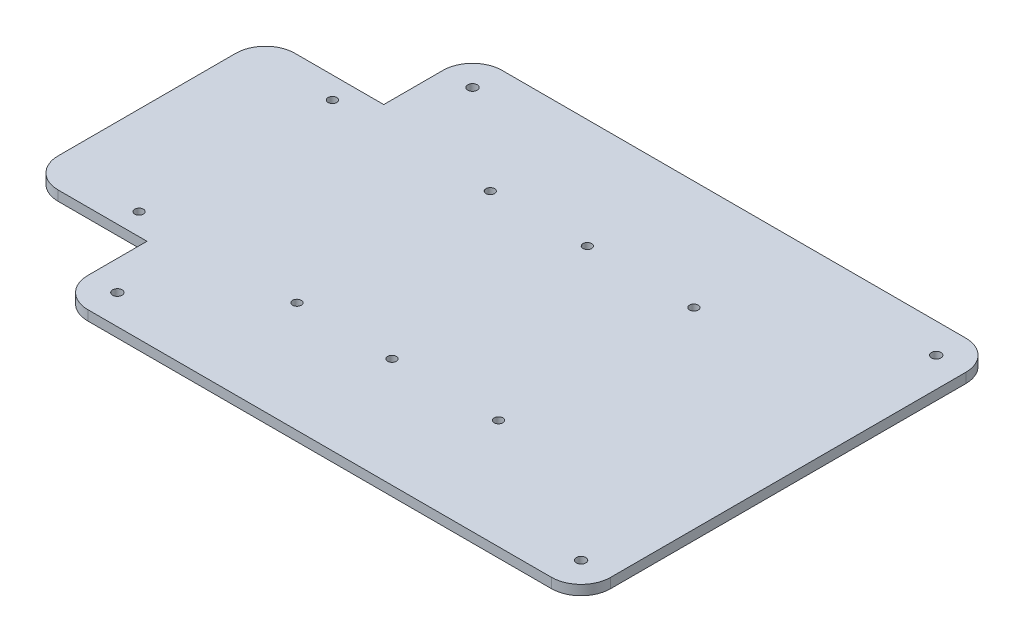
SolidWorks part; units mm, degrees
ref_plane "前视基准面" through (0, 0, 0) normal (0, 0, 1) x (1, 0, 0)
ref_plane "上视基准面" through (0, 0, 0) normal (0, 1, 0) x (1, 0, 0)
ref_plane "右视基准面" through (0, 0, 0) normal (1, 0, 0) x (0, 0, -1)
sketch "草图1" plane through (0, 0, 0) normal (0, 1, 0) x (1, 0, 0)
  line L0 (-192.7589, 0) -> (187.529, 0) construction
  line L1 (0, 157.7419) -> (0, -173.4346) construction
  line L3 (-132.5, 105) -> (132.5, 105)
  line L4 (-132.5, 105) -> (-132.5, -105)
  line L5 (-132.5, -105) -> (132.5, -105)
  line L6 (132.5, 105) -> (132.5, -105)
  dimension "D1" = 210
  dimension "D2" = 265
extrude "凸台-拉伸1" add sketch "草图1" along normal blind 5
sketch "草图3" plane through (0, 5, 0) normal (0, 1, 0) x (1, 0, 0)
  line L0 (-241.3237, 0) -> (209.8572, 0) construction
  line L1 (132.5, 105) -> (-132.5, 105) construction
  line L2 (0, -110.0116) -> (0, 100.8137) construction
  line L4 (-132.5, 105) -> (-132.5, -105) construction
  line L5 (0, -55) -> (0, 55) construction
  circle A0 centre (-117.5, 90) radius 2.4
  circle A1 centre (117.5, 90) radius 2.4
  circle A2 centre (117.5, -90) radius 2.4
  circle A3 centre (-117.5, -90) radius 2.4
  dimension "D1" = 15
  dimension "D2" = 15
extrude "切除-拉伸1" cut sketch "草图3" against normal blind 5
fillet "圆角1" radius 15 4 edges at (-132.5, 2.5, 105) (132.5, 2.5, 105) (132.5, 2.5, -105) (-132.5, 2.5, -105)
sketch "草图4" plane through (0, 0, 0) normal (0, 1, 0) x (1, 0, 0)
  line L0 (-268.8706, 0) -> (165.0385, 0) construction
  line L1 (-132.5, 90) -> (-132.5, -90) construction
  line L2 (-132.5, 60) -> (-192.5, 60)
  line L3 (-132.5, 60) -> (-132.5, -60)
  line L4 (-132.5, -60) -> (-192.5, -60)
  line L5 (-192.5, 60) -> (-192.5, -60)
  dimension "D1" = 60
  dimension "D2" = 120
extrude "凸台-拉伸3" add sketch "草图4" along normal blind 5
fillet "圆角2" radius 15 2 edges at (-192.5, 2.5, 60) (-192.5, 2.5, -60)
sketch "草图5" plane through (0, 0, 0) normal (0, 1, 0) x (1, 0, 0)
  line L0 (-406.4359, 0) -> (326.3593, 0) construction
  line L2 (0, 168.3923) -> (0, -177.4268) construction
sketch "草图6" plane through (0, 5, 0) normal (0, 1, 0) x (1, 0, 0)
  line L0 (-406.4359, 0) -> (326.3593, 0) construction
  line L1 (-192.5, 45) -> (-192.5, -45) construction
  line L2 (-2.75, 0) -> (2.75, 0) construction
  circle A0 centre (-147.5, 49) radius 2.2
  circle A1 centre (-67.5, 49) radius 2.2
  circle A2 centre (-67.5, -49) radius 2.2
  circle A3 centre (-147.5, -49) radius 2.2
  dimension "D1" = 49
  dimension "D3" = 80
  dimension "D2" = 45
extrude "切除-拉伸2" cut sketch "草图6" against normal blind 24
sketch "草图7" plane through (0, 5, 0) normal (0, 1, 0) x (1, 0, 0)
  line L0 (-406.4359, 0) -> (326.3593, 0) construction
  line L1 (-192.5, 45) -> (-192.5, -45) construction
  line L2 (-2.75, 0) -> (2.75, 0) construction
  circle A0 centre (-18.8, 49.5) radius 2.2
  circle A1 centre (35.2, 49.5) radius 2.2
  circle A2 centre (35.2, -49.5) radius 2.2
  circle A3 centre (-18.8, -49.5) radius 2.2
  dimension "D1" = 49.5
  dimension "D3" = 54
  dimension "D2" = 173.7
extrude "切除-拉伸3" cut sketch "草图7" against normal blind 10
